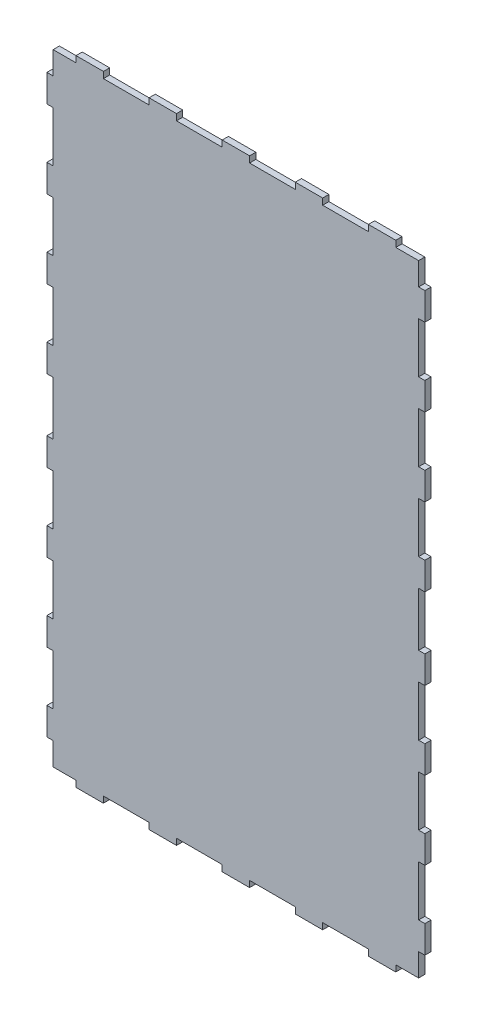
SolidWorks part; units mm, degrees
ref_plane "Front Plane" through (0, 0, 0) normal (0, 0, 1) x (1, 0, 0)
ref_plane "Top Plane" through (0, 0, 0) normal (0, 1, 0) x (1, 0, 0)
ref_plane "Right Plane" through (0, 0, 0) normal (1, 0, 0) x (0, 0, -1)
sketch "Sketch1" plane through (0, 0, 0) normal (0, 0, 1) x (1, 0, 0)
  line L1 (-127, -215.9) -> (127, -215.9)
  line L2 (-127, -215.9) -> (-127, 215.9)
  line L3 (-127, 215.9) -> (127, 215.9)
  line L4 (127, -215.9) -> (127, 215.9)
  line L5 (-127, -215.9) -> (127, 215.9) construction
  line L6 (-127, 215.9) -> (127, -215.9) construction
  point P0 (0, 0)
  dimension "D1" = 254
  dimension "D2" = 431.8
extrude "Boss-Extrude1" add sketch "Sketch1" along normal blind 4.3434
sketch "Sketch2" plane through (0, 0, 4.3434) normal (0, 0, 1) x (1, 0, 0)
  line L0 (-127, 215.9) -> (-127, -215.9) construction
  line L1 (-131.3434, 180.975) -> (-122.6566, 180.975)
  line L2 (-131.3434, 180.975) -> (-131.3434, 200.025)
  line L3 (-131.3434, 200.025) -> (-122.6566, 200.025)
  line L4 (-122.6566, 180.975) -> (-122.6566, 200.025)
  line L5 (-131.3434, 180.975) -> (-122.6566, 200.025) construction
  line L6 (-131.3434, 200.025) -> (-122.6566, 180.975) construction
  line L7 (127, 215.9) -> (-127, 215.9) construction
  line L8 (-111.125, 211.5566) -> (-92.075, 211.5566)
  line L9 (-111.125, 211.5566) -> (-111.125, 220.2434)
  line L10 (-111.125, 220.2434) -> (-92.075, 220.2434)
  line L11 (-92.075, 211.5566) -> (-92.075, 220.2434)
  line L12 (-111.125, 211.5566) -> (-92.075, 220.2434) construction
  line L13 (-111.125, 220.2434) -> (-92.075, 211.5566) construction
  line L14 (-60.325, 220.2434) -> (-41.275, 220.2434)
  line L15 (-41.275, 211.5566) -> (-41.275, 220.2434)
  line L16 (-60.325, 211.5566) -> (-41.275, 211.5566)
  line L17 (-60.325, 211.5566) -> (-60.325, 220.2434)
  line L18 (-9.525, 220.2434) -> (9.525, 220.2434)
  line L19 (9.525, 211.5566) -> (9.525, 220.2434)
  line L20 (-9.525, 211.5566) -> (9.525, 211.5566)
  line L21 (-9.525, 211.5566) -> (-9.525, 220.2434)
  line L22 (41.275, 220.2434) -> (60.325, 220.2434)
  line L23 (60.325, 211.5566) -> (60.325, 220.2434)
  line L24 (41.275, 211.5566) -> (60.325, 211.5566)
  line L25 (41.275, 211.5566) -> (41.275, 220.2434)
  line L26 (92.075, 220.2434) -> (111.125, 220.2434)
  line L27 (111.125, 211.5566) -> (111.125, 220.2434)
  line L28 (92.075, 211.5566) -> (111.125, 211.5566)
  line L29 (92.075, 211.5566) -> (92.075, 220.2434)
  line L31 (-131.3434, 145.923) -> (-122.6566, 145.923)
  line L32 (-122.6566, 126.873) -> (-122.6566, 145.923)
  line L33 (-131.3434, 126.873) -> (-122.6566, 126.873)
  line L34 (-131.3434, 126.873) -> (-131.3434, 145.923)
  line L35 (-131.3434, 91.821) -> (-122.6566, 91.821)
  line L36 (-122.6566, 72.771) -> (-122.6566, 91.821)
  line L37 (-131.3434, 72.771) -> (-122.6566, 72.771)
  line L38 (-131.3434, 72.771) -> (-131.3434, 91.821)
  line L39 (-131.3434, 37.719) -> (-122.6566, 37.719)
  line L40 (-122.6566, 18.669) -> (-122.6566, 37.719)
  line L41 (-131.3434, 18.669) -> (-122.6566, 18.669)
  line L42 (-131.3434, 18.669) -> (-131.3434, 37.719)
  line L60 (-131.3434, -16.383) -> (-122.6566, -16.383) [skipped]
  line L61 (-122.6566, -35.433) -> (-122.6566, -16.383) [skipped]
  line L62 (-131.3434, -35.433) -> (-122.6566, -35.433) [skipped]
  line L63 (-131.3434, -35.433) -> (-131.3434, -16.383) [skipped]
  line L64 (-131.3434, -70.485) -> (-122.6566, -70.485) [skipped]
  line L65 (-122.6566, -89.535) -> (-122.6566, -70.485) [skipped]
  line L66 (-131.3434, -89.535) -> (-122.6566, -89.535) [skipped]
  line L67 (-131.3434, -89.535) -> (-131.3434, -70.485) [skipped]
  line L68 (-131.3434, -124.587) -> (-122.6566, -124.587) [skipped]
  line L69 (-122.6566, -143.637) -> (-122.6566, -124.587) [skipped]
  line L70 (-131.3434, -143.637) -> (-122.6566, -143.637) [skipped]
  line L71 (-131.3434, -143.637) -> (-131.3434, -124.587) [skipped]
  line L72 (-131.3434, -178.689) -> (-122.6566, -178.689) [skipped]
  line L73 (-122.6566, -197.739) -> (-122.6566, -178.689) [skipped]
  line L74 (-131.3434, -197.739) -> (-122.6566, -197.739) [skipped]
  line L75 (-131.3434, -197.739) -> (-131.3434, -178.689) [skipped]
  point P0 (-127, 190.5)
  point P7 (-101.6, 215.9)
  point P32 (101.6, 220.2434)
  dimension "D1" = 8.6868
  dimension "D2" = 8.6868
  dimension "D3" = 19.05
  dimension "D4" = 19.05
  dimension "D5" = 25.4
  dimension "D6" = 25.4
  dimension "D7" = 5
  dimension "D8" = 8
extrude "Boss-Extrude2" add sketch "Sketch2" against normal blind 4.3434
mirror "Mirror1" about plane through (0, 0, 0) normal (1, 0, 0) of "Boss-Extrude2"
mirror "Mirror2" about plane through (0, 0, 0) normal (0, 1, 0) of "Boss-Extrude2", "Mirror1"
